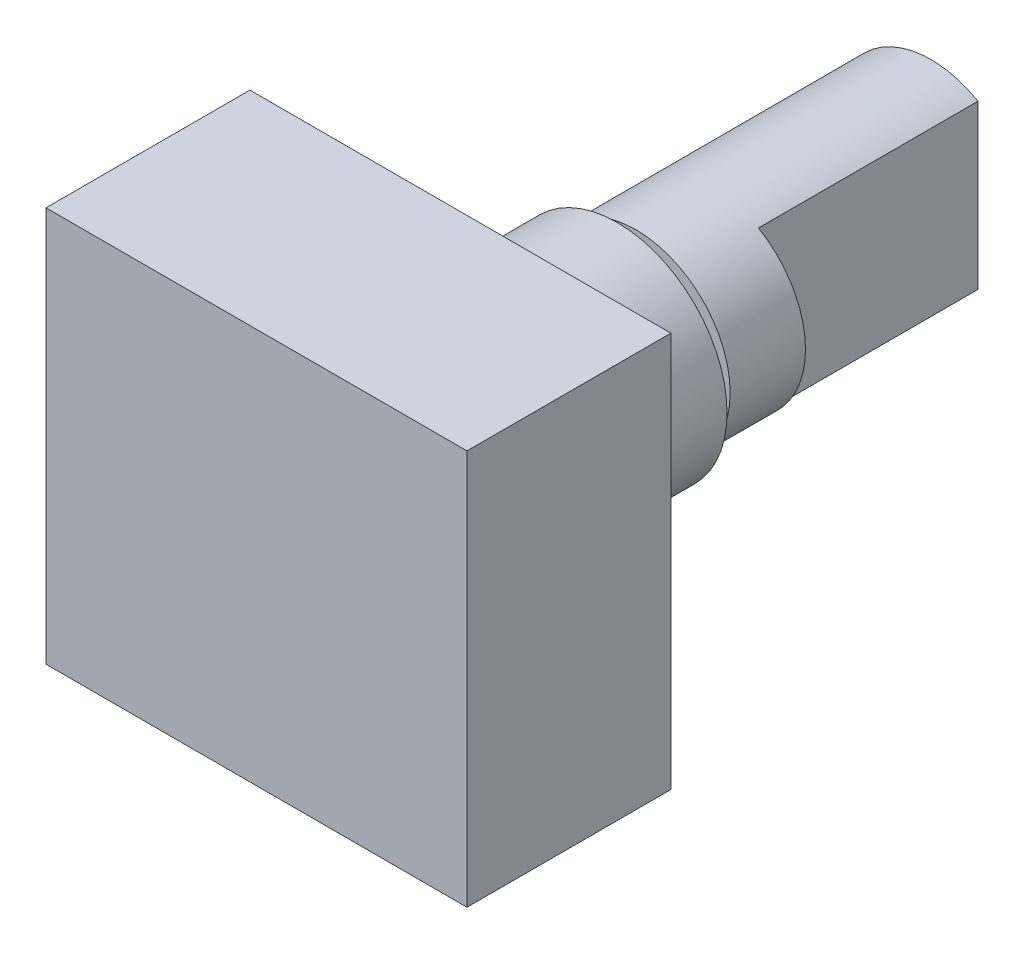
SolidWorks part; units mm, degrees
ref_plane "Front Plane" through (0, 0, 0) normal (0, 0, 1) x (1, 0, 0)
ref_plane "Top Plane" through (0, 0, 0) normal (0, 1, 0) x (1, 0, 0)
ref_plane "Right Plane" through (0, 0, 0) normal (1, 0, 0) x (0, 0, -1)
sketch "Sketch1" plane through (0, 0, 0) normal (0, 0, 1) x (1, 0, 0)
  line L1 (-6.71, 6.3) -> (6.71, 6.3)
  line L2 (-6.71, 6.3) -> (-6.71, -6.3)
  line L3 (-6.71, -6.3) -> (6.71, -6.3)
  line L4 (6.71, 6.3) -> (6.71, -6.3)
  line L5 (-6.71, 6.3) -> (6.71, -6.3) construction
  line L6 (-6.71, -6.3) -> (6.71, 6.3) construction
  point P0 (0, 0)
  dimension "D1" = 13.42
  dimension "D2" = 12.6
extrude "Boss-Extrude1" add sketch "Sketch1" along normal blind 6.5
sketch "Sketch3" plane through (0, 0, 0) normal (0, 1, 0) x (1, 0, 0)
  line L0 (0, 0) -> (0, 16.7611) construction
  line L1 (0, 0) -> (3.5, 0)
  line L2 (6.71, 0) -> (-6.71, 0) construction
  line L3 (3.5, 0) -> (3.5, 5)
  line L4 (3.5, 5) -> (2.0639, 5)
  line L5 (2.0639, 5) -> (2.0639, 5.5993)
  line L6 (2.0639, 5.5993) -> (3, 5.5993)
  line L7 (3, 5.5993) -> (3, 15)
  line L8 (3, 15) -> (0, 15)
  line L9 (0, 15) -> (0, 0)
  point P3 (0, 16.7611)
  dimension "D1" = 5
  dimension "D2" = 15
  dimension "D3" = 6
  dimension "D4" = 7
revolve "Revolve1" add sketch "Sketch3" angle 360 about L0
sketch "Sketch4" plane through (0, 0, 0) normal (0, 1, 0) x (1, 0, 0)
  line L0 (0, 0) -> (0, 16.6735) construction
  line L1 (6.71, 0) -> (-6.71, 0) construction
  line L2 (1.5, 15) -> (1.5, 8)
  line L3 (3, 15) -> (-3, 15) construction
  line L4 (3, 5.5993) -> (3, 15) construction
  line L5 (3, 8) -> (3, 15)
  line L6 (3, 15) -> (1.5, 15)
  line L7 (1.5, 8) -> (3, 8)
  line L8 (-3, 15) -> (-3, 5.5993) construction
  dimension "D1" = 4.5
  dimension "D2" = 7
extrude "Cut-Extrude1" cut sketch "Sketch4" against normal through all both and the other way through all
